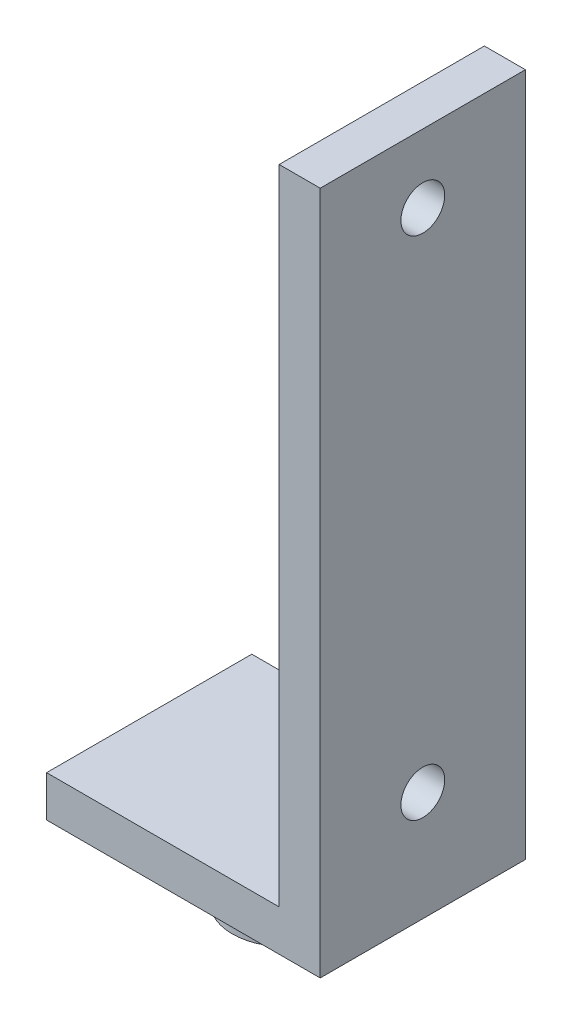
SolidWorks part; units mm, degrees
ref_plane "Front Plane" through (0, 0, 0) normal (0, 0, 1) x (1, 0, 0)
ref_plane "Top Plane" through (0, 0, 0) normal (0, 1, 0) x (1, 0, 0)
ref_plane "Right Plane" through (0, 0, 0) normal (1, 0, 0) x (0, 0, -1)
sketch "Sketch1" plane through (0, 0, 0) normal (0, 1, 0) x (1, 0, 0)
  circle A0 centre (0, 0) radius 0.875
  circle A1 centre (0, 0) radius 2.925
  circle A2 centre (0, 0) radius 3.925
  dimension "D1" = 5.85
  dimension "D2" = 1.75
  dimension "D3" = 1
extrude "Boss-Extrude1" add sketch "Sketch1" along normal blind 4 contours A2 A1 | A0
sketch "Sketch2" plane through (0, 4, 0) normal (0, 1, 0) x (1, 0, 0)
  line L1 (-10, -7.5) -> (10, -7.5)
  line L2 (-10, -7.5) -> (-10, 7.5)
  line L3 (-10, 7.5) -> (10, 7.5)
  line L4 (10, -7.5) -> (10, 7.5)
  line L5 (-10, -7.5) -> (10, 7.5) construction
  line L6 (-10, 7.5) -> (10, -7.5) construction
  point P0 (0, 0)
  dimension "D1" = 15
  dimension "D2" = 20
extrude "Boss-Extrude2" add sketch "Sketch2" along normal blind 3
sketch "Sketch3" plane through (0, 0, 0) normal (1, 0, 0) x (0, 0, -1)
  line L0 (7.5, 7) -> (7.5, 4) construction
  line L1 (-7.5, 4) -> (7.5, 4)
  line L2 (-7.5, 4) -> (-7.5, 54)
  line L3 (-7.5, 54) -> (7.5, 54)
  line L4 (7.5, 4) -> (7.5, 54)
  dimension "D1" = 50
extrude "Boss-Extrude3" add sketch "Sketch3" against normal blind 3 from surface at 10 starting at face at (10, 5.5, 0)
hole_wizard "Ø3.2 (3.2) Diameter Hole1" positions "Sketch4" profile "Sketch5" hole size "Ø3.2" standard "ANSI Metric"
sketch "Sketch4" plane through (10, 0, 0) normal (1, 0, 0) x (0, 0, -1)
  line L1 (7.5, 54) -> (-7.5, 54) construction
  line L2 (0, 4) -> (0, 54) construction
  line L3 (-7.5, 4) -> (7.5, 4) construction
  point P0 (0, 12)
  point P2 (0, 49)
  point P23 (0, 0)
  point P24 (0, 0)
  dimension "D1" = 37
  dimension "D2" = 5
sketch "Sketch5" plane through (10, 12, 0) normal (0, 1, 0) x (0, 0, -1)
  line L0 (0, 0) -> (0, 4.9614)
  line L1 (0, 4.9614) -> (1.6, 4)
  line L2 (1.6, 4) -> (1.6, 0)
  line L5 (1.6, 0) -> (0, 0)
  line L10 (0, 4.9614) -> (-1.6, 4) construction
  line L11 (0, -6.35) -> (0, 107.95) construction
  dimension "Hole Dia." = 3.2
  dimension "Hole Depth" = 4
  dimension "Drill Angle" = 118
equation "\"D1@Sketch1\"=5.75mm+0.1mm"
equation "\"D2@Sketch1\"=1.85 - 0.1"
